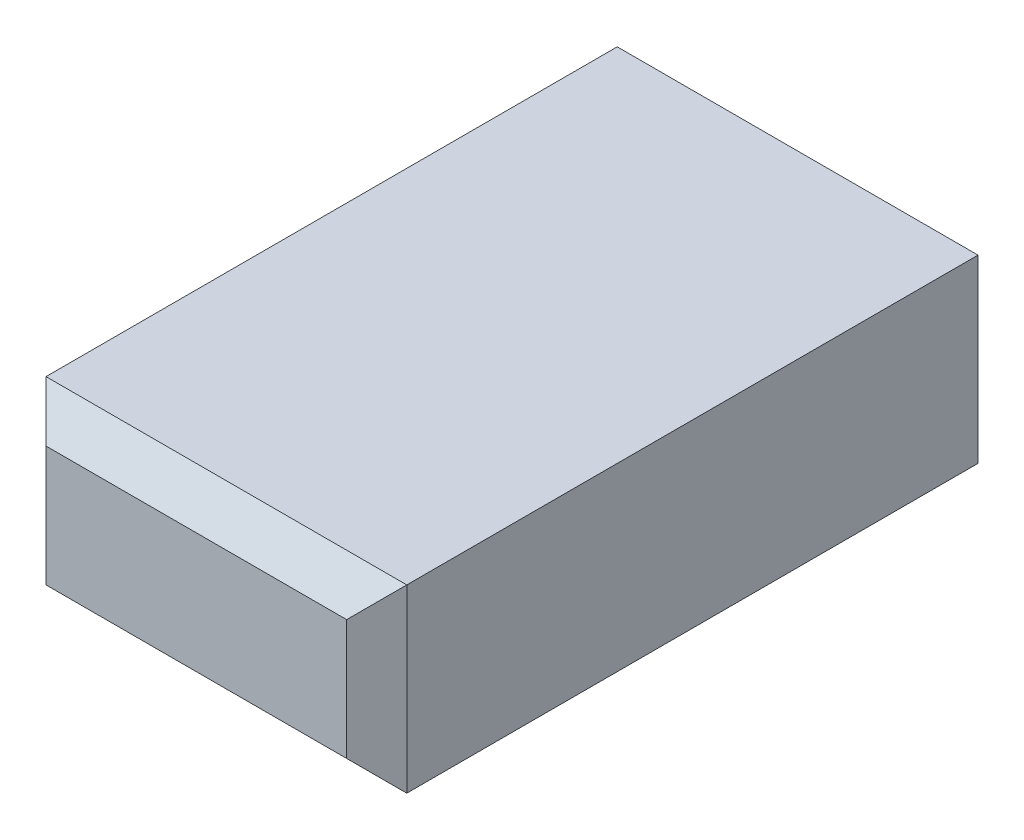
SolidWorks part; units mm, degrees
ref_plane "Front Plane" through (0, 0, 0) normal (0, 0, 1) x (1, 0, 0)
ref_plane "Top Plane" through (0, 0, 0) normal (0, 1, 0) x (1, 0, 0)
ref_plane "Right Plane" through (0, 0, 0) normal (1, 0, 0) x (0, 0, -1)
sketch "Esquisse1" plane through (0, 0, 0) normal (0, 0, 1) x (1, 0, 0)
  line L1 (3, -1.5) -> (-3, -1.5)
  line L2 (3, -1.5) -> (3, 1.5)
  line L3 (3, 1.5) -> (-3, 1.5)
  line L4 (-3, -1.5) -> (-3, 1.5)
  line L5 (3, -1.5) -> (-3, 1.5) construction
  line L6 (3, 1.5) -> (-3, -1.5) construction
  point P0 (0, 0)
  dimension "D1" = 6
  dimension "D2" = 3
extrude "Boss.-Extru.1" add sketch "Esquisse1" along normal blind 10
chamfer "Chanfrein1" distance 0.5 angle 45 4 edges at (0, 1.5, 10) (3, 0, 10) (0, -1.5, 10) (-3, 0, 10)
